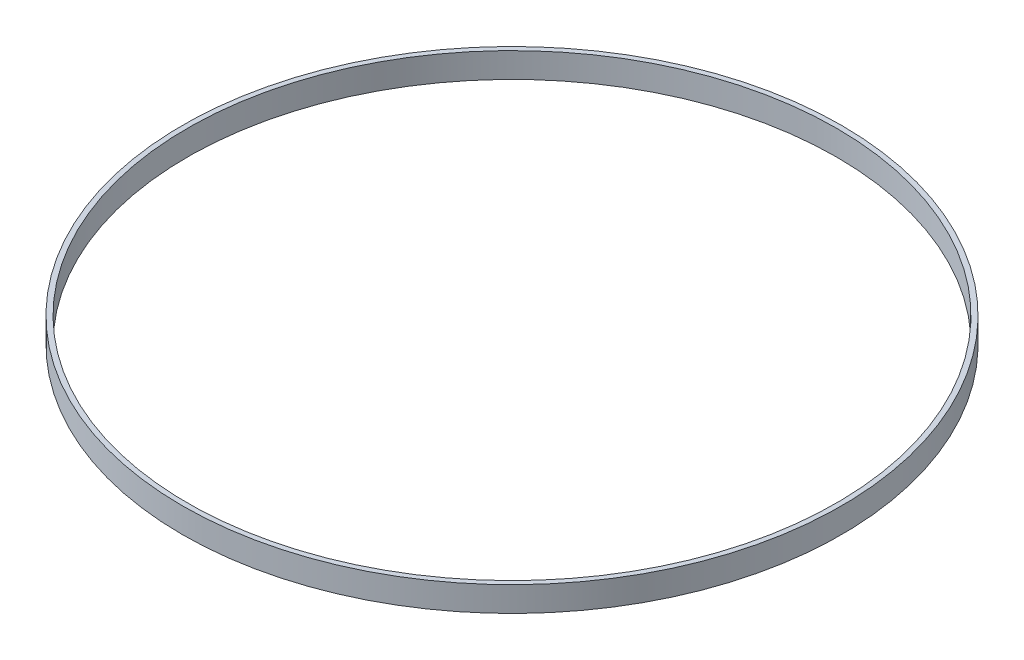
SolidWorks part; units mm, degrees
ref_plane "Front Plane" through (0, 0, 0) normal (0, 0, 1) x (1, 0, 0)
ref_plane "Top Plane" through (0, 0, 0) normal (0, 1, 0) x (1, 0, 0)
ref_plane "Right Plane" through (0, 0, 0) normal (1, 0, 0) x (0, 0, -1)
sketch "Sketch1" plane through (0, 0, 0) normal (0, 0, 1) x (1, 0, 0)
  line L0 (0, 0) -> (0, 10) construction
  line L1 (0, 10) -> (130, 10) construction
  line L2 (130, 10) -> (130, 0)
  line L3 (130, 0) -> (132, 0)
  line L4 (132, 0) -> (132, 10)
  line L5 (132, 10) -> (130, 10)
  dimension "D1" = 10
  dimension "D2" = 130
  dimension "D3" = 2
revolve "Revolve1" add sketch "Sketch1" angle 360 about L0
